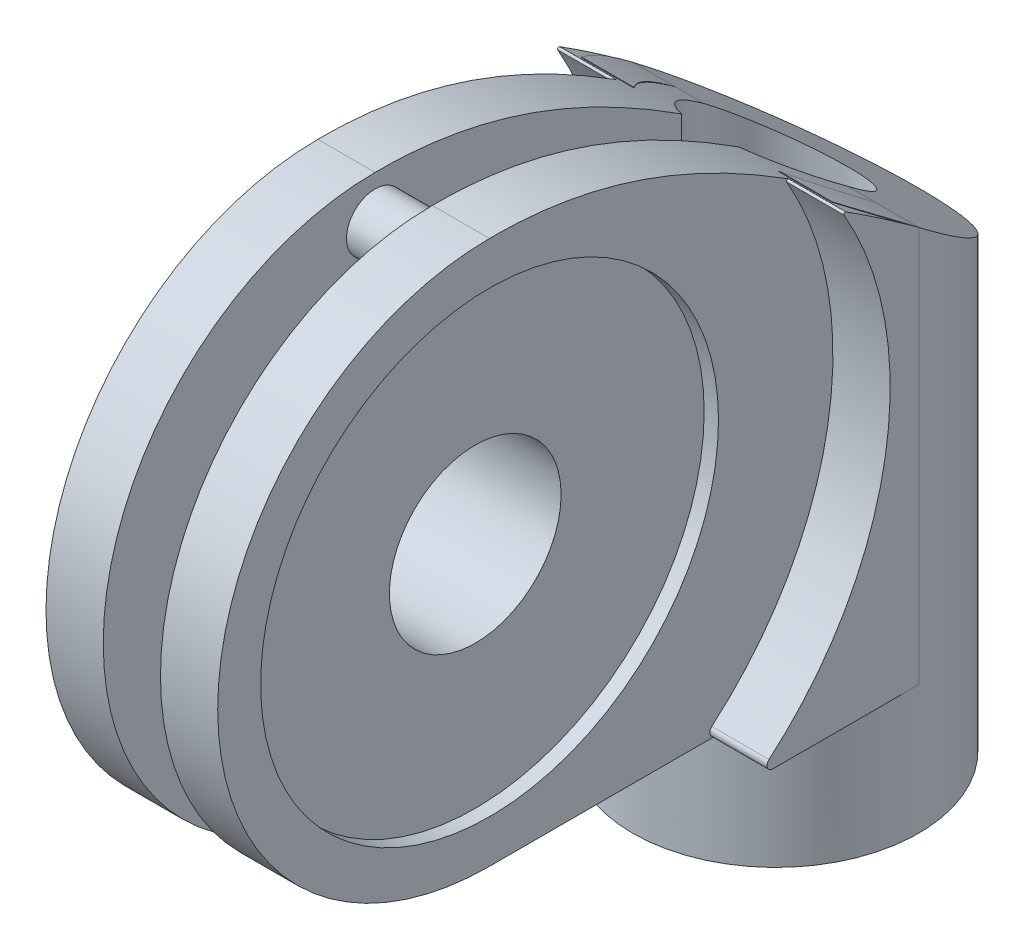
SolidWorks part; units mm, degrees
material "Copper"
ref_plane "Front Plane" through (0, 0, 0) normal (0, 0, 1) x (1, 0, 0)
ref_plane "Top Plane" through (0, 0, 0) normal (0, 1, 0) x (1, 0, 0)
ref_plane "Right Plane" through (0, 0, 0) normal (1, 0, 0) x (0, 0, -1)
sketch "Sketch1" plane through (0, 0, 0) normal (0, 1, 0) x (1, 0, 0)
  circle A0 centre (0, 0) radius 5
  circle A1 centre (0, 0) radius 3.5
  dimension "D1" = 7
  dimension "D2" = 10
extrude "Boss-Extrude1" add sketch "Sketch1" along normal blind 20
sketch "Sketch2" plane through (0, 0, 0) normal (1, 0, 0) x (0, 0, -1)
  line L0 (-13, 4.5) -> (-5, 4.5)
  line L1 (-5, 20) -> (-5, 0) construction
  line L2 (5, 20) -> (-5, 20) construction
  line L3 (5, 0) -> (5, 20) construction
  line L4 (-5, 4.5) -> (5, 4.5)
  line L5 (5, 4.5) -> (5, 14.5236)
  arc A0 (-13, 23.5) -> (-13, 4.5) centre (-13, 14) ccw
  spline S0 degree 3 poles (-13, 23.5) (-5.7964, 23.5688) (-0.2926, 18.5088) (5, 14.5236) knots 0 0 0 0 1 1 1 1
extrude "Boss-Extrude2" add sketch "Sketch2" along normal blind 5 and the other way blind 5
sketch "Sketch3" plane through (5, 0, 0) normal (1, 0, 0) x (0, 0, -1)
  line L0 (5, 14.5236) -> (0, 18.3349)
  line L1 (-3.4346, 20.6218) -> (-1.0112, 24.8199)
  line L2 (-1.0112, 24.8199) -> (8.1471, 19.5332)
  line L3 (8.1471, 19.5332) -> (5, 14.5236)
  arc A0 (0, 18.3349) -> (-3.4346, 20.6218) centre (-19.5912, -7.3665) ccw
  spline S0 degree 3 poles (0, 18.3349) (-3.8486, 21.1417) (-8.0177, 23.5476) (-13, 23.5) knots 0.30836 0.30836 0.30836 0.30836 1 1 1 1 construction
extrude "Cut-Extrude1" cut sketch "Sketch3" against normal blind 11
sketch "Sketch4" plane through (0, 0, 0) normal (0, -1, 0) x (1, 0, 0)
  line L0 (5, 0) -> (9.2304, 0)
  line L1 (-9.2304, 0) -> (-5, 0)
  arc A0 (-5, 0) -> (5, 0) centre (0, 0) ccw
  arc A1 (-9.2304, 0) -> (9.2304, 0) centre (0, 0) ccw
  circle A4 centre (0, 0) radius 2.5
extrude "Cut-Extrude2" cut sketch "Sketch4" against normal blind 22
sketch "Sketch5" plane through (5, 0, 0) normal (1, 0, 0) x (0, 0, -1)
  circle A0 centre (-13, 14) radius 12
extrude "Cut-Extrude3" cut sketch "Sketch5" against normal blind 2
mirror "Mirror1" about plane through (0, 0, 0) normal (1, 0, 0) of "Cut-Extrude3"
sketch "Sketch7" plane through (0, 0, 0) normal (1, 0, 0) x (0, 0, -1)
  circle A0 centre (-13, 14) radius 13
extrude "Cut-Extrude4" cut sketch "Sketch7" against normal blind 1 and the other way blind 1
sketch "Sketch8" plane through (3, 0, 0) normal (1, 0, 0) x (0, 0, -1)
  circle A0 centre (-13, 14) radius 3
extrude "Cut-Extrude5" cut sketch "Sketch8" against normal blind 12
sketch "Sketch9" plane through (3, 0, 0) normal (1, 0, 0) x (0, 0, -1)
  circle A0 centre (-13, 14) radius 8
extrude "Cut-Extrude6" cut sketch "Sketch9" against normal blind 0.5
mirror "Mirror2" about plane through (0, 0, 0) normal (1, 0, 0) of "Cut-Extrude6"
sketch "Sketch10" plane through (1, 0, 0) normal (-1, 0, 0) x (0, 0, 1)
  circle A0 centre (13, 22) radius 1
  circle A1 centre (13, 14) radius 8 construction
  circle A2 centre (13, 14) radius 8 construction
extrude "Boss-Extrude3" add sketch "Sketch10" along normal up to surface (2 mm away) up to face at (-1, 14, 10)
fillet "Fillet2" radius 0.2 2 edges at (-4, 4.5, 5.6686) (4, 4.5, 5.6686)
fillet "Fillet3" radius 0.05 2 edges at (4, 20.1862, 2.7174) (-4, 20.1862, 2.7174)
ref_plane "Plane2" through (0, 0, -5) normal (0, 0, 1) x (1, 0, 0)
sketch "Sketch12" plane through (0, 0, -5) normal (0, 0, 1) x (1, 0, 0)
  line L0 (0, 0) -> (0.5, 0)
  line L1 (-5, 0) -> (5, 0) construction
  line L2 (0, 0) -> (-0.5, 0)
  line L3 (-0.5, 0) -> (-0.5, 1)
  line L4 (-0.5, 1) -> (0.5, 1)
  line L5 (0.5, 1) -> (0.5, 0)
extrude "Cut-Extrude7" cut sketch "Sketch12" along normal blind 2.5
sketch "Sketch13" plane through (1, 0, 0) normal (-1, 0, 0) x (0, 0, 1)
  circle A0 centre (13, 14) radius 3
  circle A1 centre (13, 14) radius 4
extrude "Boss-Extrude4" add sketch "Sketch13" along normal up to surface (2 mm away) up to face at (-1, 22, 12)
